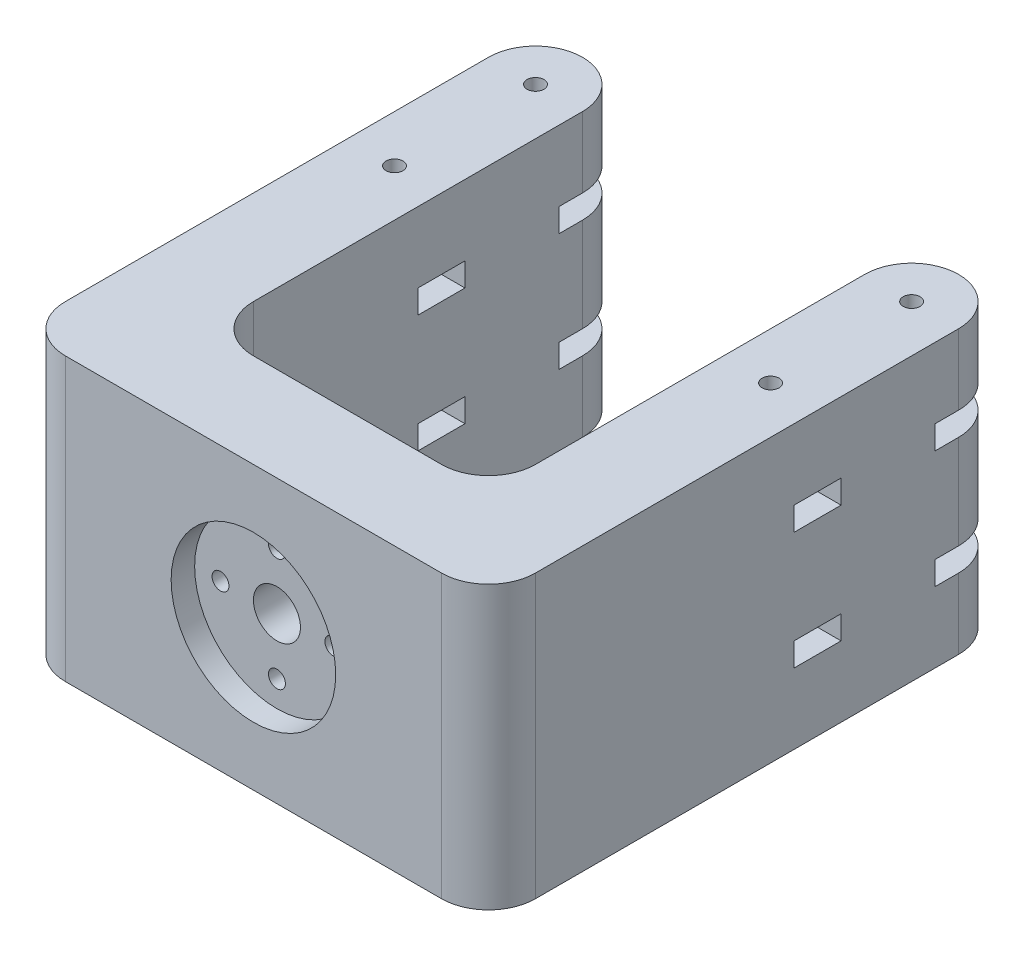
SolidWorks part; units mm, degrees
material "ESUN PLA +"
ref_plane "Front Plane" through (0, 0, 0) normal (0, 0, 1) x (1, 0, 0)
ref_plane "Top Plane" through (0, 0, 0) normal (0, 1, 0) x (1, 0, 0)
ref_plane "Right Plane" through (0, 0, 0) normal (1, 0, 0) x (0, 0, -1)
sketch "Sketch1" plane through (0, 0, 0) normal (0, 1, 0) x (1, 0, 0)
  line L0 (-50, 0) -> (50, 0)
  line L1 (50, 0) -> (50, 100)
  line L2 (50, 100) -> (30, 100) construction
  line L3 (30, 100) -> (30, 20)
  line L4 (30, 20) -> (-30, 20)
  line L5 (-30, 20) -> (-30, 100)
  line L6 (-30, 100) -> (-50, 100) construction
  line L7 (-50, 100) -> (-50, 0)
  arc A0 (-50, 100) -> (-30, 100) centre (-40, 100) cw
  arc A1 (30, 100) -> (50, 100) centre (40, 100) cw
  point P4 (0, 0)
  dimension "D6" = 80
  dimension "D1" = 20
  dimension "D2" = 20
  dimension "D3" = 20
  dimension "D4" = 100
  dimension "D5" = 20
extrude "Boss-Extrude1" add sketch "Sketch1" along normal mid plane 60
fillet "Fillet1" radius 10 4 edges at (30, 0, -20) (-30, 0, -20) (50, 0, 0) (-50, 0, 0)
sketch "Sketch3" plane through (0, 0, 0) normal (0, 0, 1) x (1, 0, 0)
  circle A0 centre (0, 0) radius 5
  dimension "D1" = 10
extrude "Cut-Extrude1" cut sketch "Sketch3" against normal through all and the other way through all
sketch "Sketch4" plane through (0, 0, 0) normal (0, 0, 1) x (1, 0, 0)
  circle A0 centre (0, 0) radius 17.5
  dimension "D1" = 35
extrude "Cut-Extrude2" cut sketch "Sketch4" against normal blind 5
sketch "Sketch5" plane through (0, 0, -5) normal (0, 0, 1) x (1, 0, 0)
  circle A0 centre (0, -12) radius 1.8
  dimension "D1" = 12
  dimension "D2" = 3.6
extrude "Cut-Extrude3" cut sketch "Sketch5" against normal blind 5
pattern_circular "CirPattern1" count 4 over 360 about axis through (0, 0, 0) along (0, 0, 1) of "Cut-Extrude3"
sketch "Sketch6" plane through (0, 30, 0) normal (0, 1, 0) x (1, 0, 0)
  circle A0 centre (-40, 100) radius 1.8
  circle A1 centre (-40, 70) radius 1.8
  dimension "D1" = 3.6
  dimension "D2" = 30
extrude "Cut-Extrude4" cut sketch "Sketch6" against normal through all
ref_plane "Plane1" through (0, 15, 0) normal (0, 1, 0) x (1, 0, 0)
sketch "Sketch7" plane through (0, 15, 0) normal (0, 1, 0) x (1, 0, 0)
  line L1 (-50, 105) -> (-30, 105) construction
  line L2 (-50, 105) -> (-50, 95)
  line L3 (-50, 95) -> (-30, 95)
  line L4 (-30, 105) -> (-30, 95)
  line L5 (-50, 105) -> (-30, 95) construction
  line L6 (-50, 95) -> (-30, 105) construction
  line L7 (-50, 75) -> (-30, 75)
  line L8 (-50, 75) -> (-50, 65)
  line L9 (-50, 65) -> (-30, 65)
  line L10 (-30, 75) -> (-30, 65)
  line L11 (-50, 75) -> (-30, 65) construction
  line L12 (-50, 65) -> (-30, 75) construction
  line L13 (-30, 30) -> (-30, 100) construction
  arc A0 (-50, 105) -> (-30, 105) centre (-40, 105) cw
  point P0 (-40, 100)
  point P5 (-40, 70)
  dimension "D1" = 10
extrude "Cut-Extrude5" cut sketch "Sketch7" against normal blind 5
mirror "Mirror1" about plane through (0, 0, 0) normal (0, 1, 0) of "Cut-Extrude5"
mirror "Mirror2" about plane through (0, 0, 0) normal (1, 0, 0) of "Cut-Extrude4", "Cut-Extrude5", "Mirror1"
